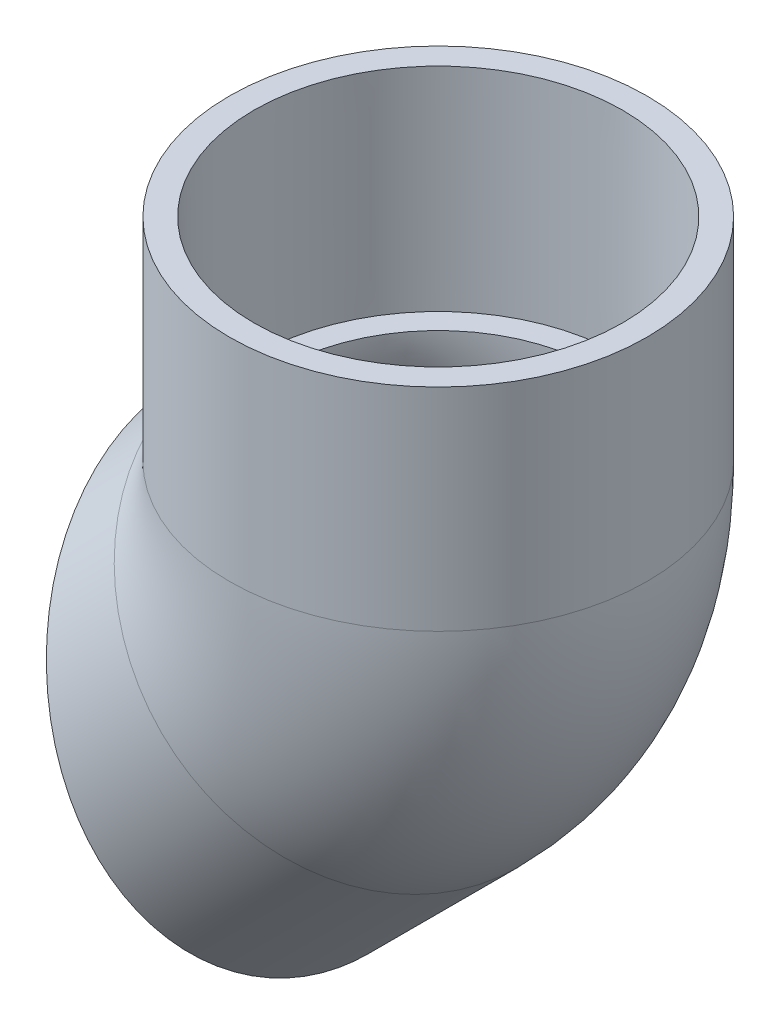
SolidWorks part; units mm, degrees
ref_plane "Front Plane" through (0, 0, 0) normal (0, 0, 1) x (1, 0, 0)
ref_plane "Top Plane" through (0, 0, 0) normal (0, 1, 0) x (1, 0, 0)
ref_plane "Right Plane" through (0, 0, 0) normal (1, 0, 0) x (0, 0, -1)
sketch "Sketch0" plane through (0, 0, 0) normal (0, 0, 1) x (1, 0, 0)
  line L0 (-35.8312, -35.8312) -> (0, 0) construction
  line L1 (0, 0) -> (0, 50.673) construction
  line L2 (-11.2253, -11.2253) -> (0, 0) construction
  line L3 (0, 0) -> (0, 15.875) construction
  line L4 (-60.1228, -11.5396) -> (-11.5396, -60.1228) construction
  line L5 (-32.4995, 10.0489) -> (-57.2671, -14.3954) construction
  line L6 (-32.4995, 10.0489) -> (10.0489, -32.4995) construction
  line L7 (10.0489, -32.4995) -> (-14.3954, -57.2671) construction
  line L8 (-57.2671, -14.3954) -> (-14.3954, -57.2671) construction
  line L9 (-34.3535, 50.673) -> (34.3535, 50.673) construction
  line L10 (-30.3149, 50.673) -> (30.3149, 50.673) construction
  line L11 (30.3149, 50.673) -> (30.0863, 15.875) construction
  line L12 (30.0863, 15.875) -> (-30.0863, 15.875) construction
  line L13 (-30.0863, 15.875) -> (-30.3149, 50.673) construction
  line L14 (-29.7875, 7.3369) -> (7.3369, -29.7875) construction
  line L18 (-26.2509, 15.875) -> (26.2509, 15.875) construction
  dimension "D1" = 45
  dimension "H" = 50.673
  dimension "J" = 15.875
  dimension "M" = 68.707
  dimension "OD A" = 60.6298
  dimension "OD B" = 60.1726
  dimension "ID" = 52.5018
sketch "Sketch1" plane through (0, 0, 0) normal (0, 0, 1) x (1, 0, 0)
  line L0 (-35.8312, -35.8312) -> (0, 0) construction
  line L1 (-35.8312, -35.8312) -> (0, 0) construction
  line L3 (-11.5396, -60.1228) -> (13.0663, -35.5169)
  line L4 (-11.5396, -60.1228) -> (-14.3954, -57.2671)
  line L5 (-14.3954, -57.2671) -> (10.0489, -32.4995)
  line L6 (13.0663, -35.5169) -> (10.0489, -32.4995)
revolve "Revolve1" add sketch "Sketch1" angle 360 about L1
sketch "Sketch2" plane through (0, 0, 0) normal (0, 0, 1) x (1, 0, 0)
  line L0 (30.3149, 50.673) -> (30.0863, 15.875)
  line L1 (30.0863, 15.875) -> (34.3535, 15.875)
  line L2 (34.3535, 15.875) -> (34.3535, 50.673)
  line L3 (34.3535, 50.673) -> (30.3149, 50.673)
  line L4 (0, 0) -> (0, 50.673) construction
  line L5 (0, 0) -> (0, 50.673) construction
revolve "Revolve2" add sketch "Sketch2" angle 360 about L5
sketch "Sketch3" plane through (-11.2253, -11.2253, 0) normal (0.7071, 0.7071, 0) x (0, 0, -1)
  circle A0 centre (0, 0) radius 26.2509
  circle A1 centre (0, 0) radius 34.3535
sketch "Sketch4" plane through (0, 0, 0) normal (0, 0, 1) x (1, 0, 0)
  line L0 (-35.8312, -35.8312) -> (0, 0) construction
  line L1 (0, 0) -> (0, 50.673) construction
  line L2 (-35.8312, -35.8312) -> (-11.2253, -11.2253) construction
  line L3 (0, 15.875) -> (0, 50.673) construction
  arc A0 (-11.2253, -11.2253) -> (0, 15.875) centre (-38.3256, 15.875) ccw
sweep "Sweep1" add profiles "Sketch3" path "Sketch4"
sketch "Sketch5" plane through (0, 0, 0) normal (0, 0, 1) x (1, 0, 0)
  line L0 (-42.1623, 6.4209) -> (-60.1228, -11.5396)
  line L1 (-35.5169, 13.0663) -> (-60.1228, -11.5396) construction
  line L2 (-60.1228, -11.5396) -> (-11.5396, -60.1228)
  line L3 (-11.5396, -60.1228) -> (-42.1623, 6.4209)
  dimension "D1" = 25.4
extrude "Cut-Extrude1" cut sketch "Sketch5" against normal through all and the other way through all
